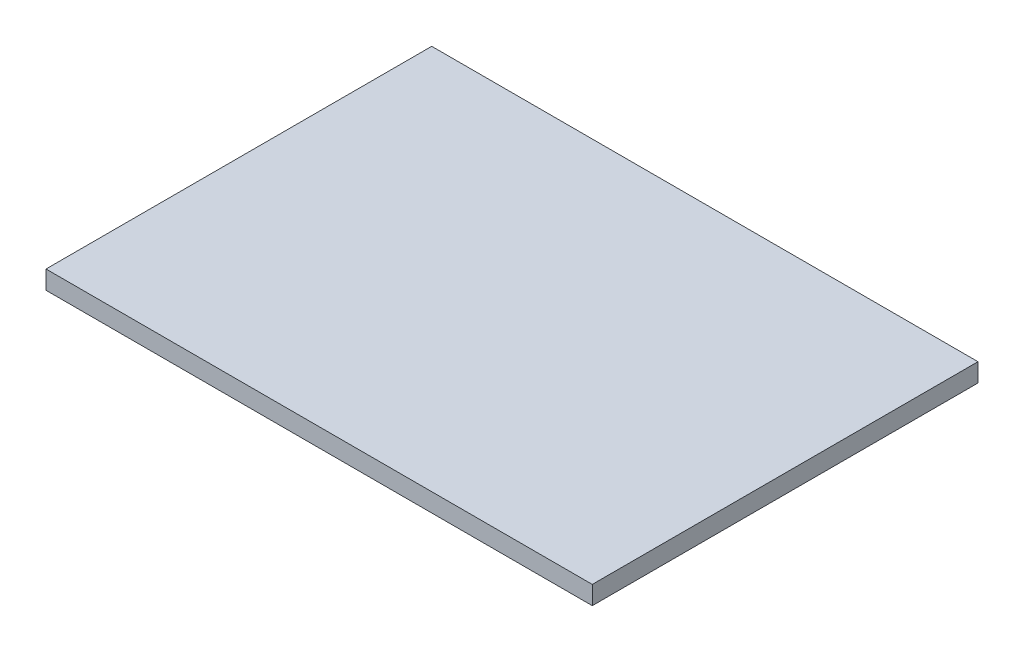
SolidWorks part; units mm, degrees
ref_plane "Front Plane" through (0, 0, 0) normal (0, 0, 1) x (1, 0, 0)
ref_plane "Top Plane" through (0, 0, 0) normal (0, 1, 0) x (1, 0, 0)
ref_plane "Right Plane" through (0, 0, 0) normal (1, 0, 0) x (0, 0, -1)
sketch "Sketch2" plane through (0, 0, 0) normal (0, 1, 0) x (1, 0, 0)
  line L1 (-148, -104.5) -> (148, -104.5)
  line L2 (-148, -104.5) -> (-148, 104.5)
  line L3 (-148, 104.5) -> (148, 104.5)
  line L4 (148, -104.5) -> (148, 104.5)
  line L5 (-148, -104.5) -> (148, 104.5) construction
  line L6 (-148, 104.5) -> (148, -104.5) construction
  point P0 (0, 0)
  dimension "D1" = 296
  dimension "D2" = 209
extrude "Extrude1" add sketch "Sketch2" along normal blind 10
